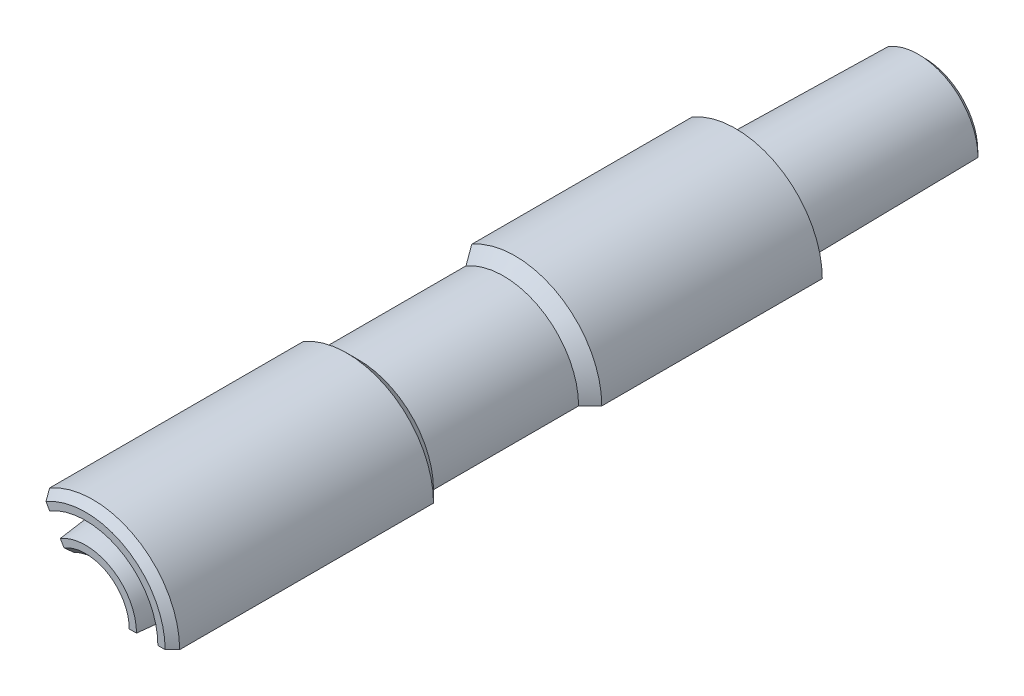
SolidWorks part; units mm, degrees
ref_plane "정면" through (0, 0, 0) normal (0, 0, 1) x (1, 0, 0)
ref_plane "윗면" through (0, 0, 0) normal (0, 1, 0) x (1, 0, 0)
ref_plane "우측면" through (0, 0, 0) normal (1, 0, 0) x (0, 0, -1)
sketch "스케치1" plane through (0, 0, 0) normal (0, 1, 0) x (1, 0, 0)
  line L0 (0, 0) -> (3, 0) construction
  line L1 (2.525, -30.375) -> (2.525, -38.375)
  line L2 (2.525, -38.375) -> (3, -38.85)
  line L3 (3, -38.85) -> (3, -48.85)
  line L4 (3, -48.85) -> (2.525, -49.325)
  line L5 (2.525, -49.325) -> (2.525, -57.325)
  line L6 (2.525, -57.325) -> (3, -57.8)
  line L7 (3, -57.8) -> (3.5, -57.8)
  line L8 (3.5, -57.8) -> (3.9604, -53.8)
  line L9 (3.9604, -53.8) -> (4.6442, -53.8)
  line L10 (4.6442, -53.8) -> (4.975, -57.8)
  line L11 (4.975, -57.8) -> (5.975, -57.8)
  line L12 (5.975, -57.8) -> (5.975, -39.8)
  line L13 (5.975, -39.8) -> (5.175, -39)
  line L14 (5.175, -39) -> (5.175, -29)
  line L15 (5.175, -29) -> (5.975, -28.2)
  line L16 (5.975, -28.2) -> (5.975, -13)
  line L17 (5.975, -13) -> (5.475, -13)
  line L18 (5.475, -13) -> (5.175, -19)
  line L19 (5.175, -19) -> (4.4306, -19)
  line L20 (4.4306, -19) -> (4.1, 0)
  line L21 (4.1, 0) -> (3, 0)
  line L22 (0, 0) -> (0, -57.8) construction
  line L23 (0, -57.8) -> (3, -57.8) construction
  line L24 (3, -48.85) -> (3, -57.8) construction
  line L25 (2.525, -30.375) -> (3, -29.9)
  line L26 (3, -29.9) -> (3, -19.9)
  line L27 (3, -19.9) -> (2.525, -19.425)
  line L28 (2.525, -19.425) -> (2.525, -11.425)
  line L29 (2.525, -11.425) -> (3, -10.95)
  line L30 (3, -10.95) -> (3, 0)
  dimension "D1" = 135
  dimension "D2" = 5.05
  dimension "D3" = 6
  dimension "D4" = 135
  dimension "D5" = 11.95
  dimension "D6" = 8
  dimension "D7" = 10
  dimension "D8" = 4
  dimension "D9" = 57.8
  dimension "D10" = 0.5
  dimension "D11" = 1
  dimension "D12" = 1.1
  dimension "D13" = 0.5
  dimension "D14" = 6
  dimension "D15" = 135
  dimension "D16" = 135
  dimension "D17" = 10
  dimension "D18" = 135
  dimension "D19" = 8
  dimension "D20" = 10
  dimension "D21" = 0.8
  dimension "D22" = 18
  dimension "D23" = 10
revolve "회전1" add sketch "스케치1" angle 120 about L22
chamfer "모따기1" distance 0.4 angle 45 1 edges at (2.05, 3.5507, 0)
chamfer "모따기2" distance 0.5 angle 45 1 edges at (2.9875, 5.1745, 57.8)
